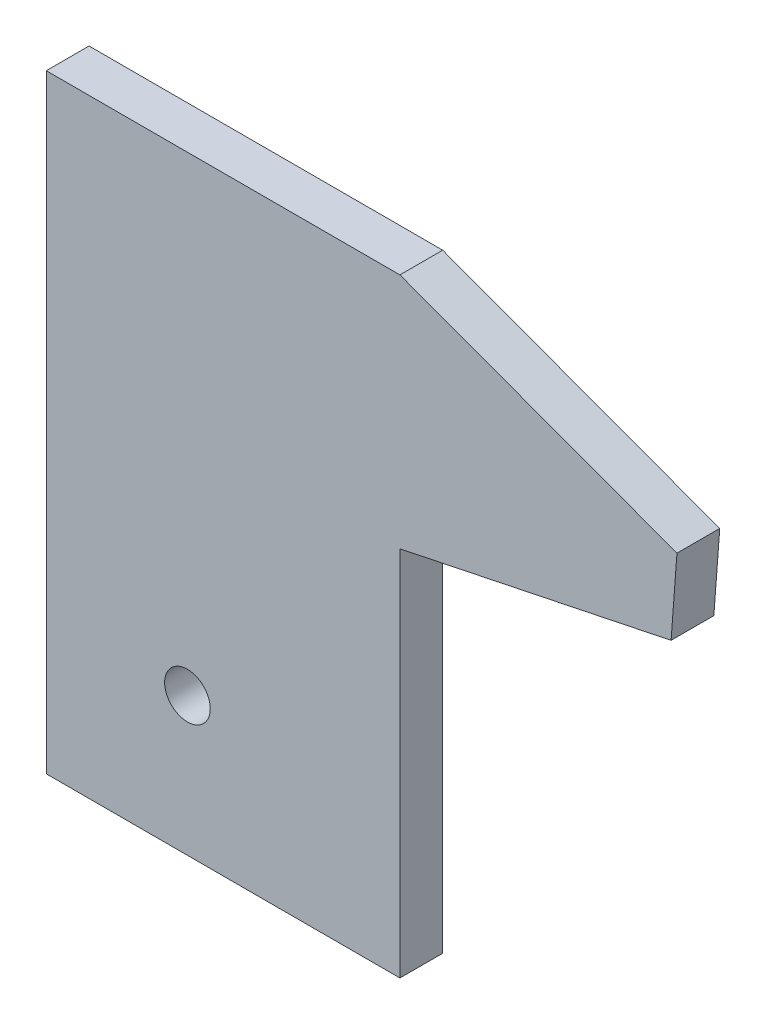
SolidWorks part; units mm, degrees
ref_plane "前视基准面" through (0, 0, 0) normal (0, 0, 1) x (1, 0, 0)
ref_plane "上视基准面" through (0, 0, 0) normal (0, 1, 0) x (1, 0, 0)
ref_plane "右视基准面" through (0, 0, 0) normal (1, 0, 0) x (0, 0, -1)
sketch "Sketch1" plane through (0, 0, 0) normal (0, 0, 1) x (1, 0, 0)
  line L0 (-194.2357, -25) -> (-191.2357, -25) construction
  line L1 (-160.3357, -67.7) -> (-185.1357, -67.7)
  line L2 (-160.3357, -67.7) -> (-160.3357, -41.6352)
  line L3 (-160.3357, -25) -> (-185.1357, -25)
  line L4 (-185.1357, -67.7) -> (-185.1357, -25)
  line L5 (-185.2357, -68) -> (-185.2357, -52.9797) construction
  line L6 (-160.2357, -68) -> (-160.2357, -44.7076) construction
  line L7 (-185.2357, -68) -> (-160.2357, -68) construction
  line L8 (-160.3357, -25) -> (-140.9079, -32.1848)
  line L9 (-141.3198, -37.6865) -> (-160.3357, -41.6352)
  line L10 (-140.9079, -32.1848) -> (-141.3198, -37.6865)
  circle A0 centre (-175.2357, -58) radius 1.6
  point P15 (-131.5287, -35.6533)
  point P16 (-131.5287, -35.6533)
  dimension "D4" = 3.2
  dimension "D1" = 0.1
  dimension "D2" = 0.1
  dimension "D3" = 0.3
extrude "Boss-Extrude1" add sketch "Sketch1" along normal blind 3
